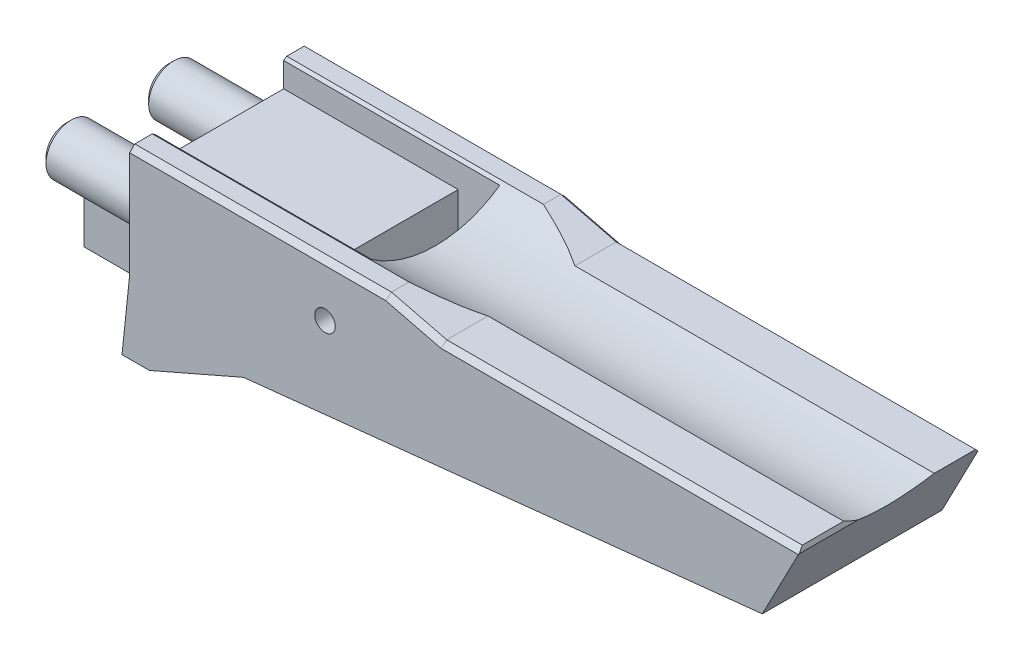
SolidWorks part; units mm, degrees
ref_plane "정면" through (0, 0, 0) normal (0, 0, 1) x (1, 0, 0)
ref_plane "윗면" through (0, 0, 0) normal (0, 1, 0) x (1, 0, 0)
ref_plane "우측면" through (0, 0, 0) normal (1, 0, 0) x (0, 0, -1)
sketch "스케치1" plane through (0, 0, 0) normal (0, 0, 1) x (1, 0, 0)
  line L0 (0, 0) -> (50, 0)
  line L1 (50, 0) -> (60.7742, -2.6631)
  line L2 (60.7742, -2.6631) -> (130.7742, -2.6631)
  line L3 (130.7742, -2.6631) -> (123.2398, -17.1695)
  line L4 (123.2398, -17.1695) -> (22.1682, -27.7991)
  line L5 (0, 0) -> (0, -21.57)
  line L6 (0, -21.57) -> (-1.496, -35.8031)
  line L7 (-1.496, -35.8031) -> (3.8284, -35.8031)
  line L8 (3.8284, -35.8031) -> (22.1682, -27.7991)
  dimension "D1" = 174
  dimension "D2" = 50
  dimension "D3" = 70
  dimension "D4" = 21.57
extrude "보스-돌출1" add sketch "스케치1" along normal mid plane 35 contours L0 L1 L2 L3 L4 L8 L7 L6 L5
sketch "스케치2" plane through (0, 0, 0) normal (0, 0, 1) x (1, 0, 0)
  line L0 (0, 0) -> (0, -5.2)
  line L1 (0, 0) -> (0, -21.57) construction
  line L2 (0, -5.2) -> (34, -5.2)
  line L3 (34, -5.2) -> (34, -18.4)
  line L4 (34, -18.4) -> (42.1, -18.4)
  line L5 (42.1, -18.4) -> (42.1, 0)
  line L6 (0, 0) -> (50, 0) construction
  line L7 (42.1, 0) -> (0, 0)
  dimension "D1" = 8.1
  dimension "D2" = 42.1
  dimension "D3" = 18.4
  dimension "D4" = 5.2
extrude "컷-돌출1" cut sketch "스케치2" against normal mid plane 25 contours L2 L3 L4 L5 L7 L0
sketch "스케치3" plane through (0, 0, 0) normal (1, 0, 0) x (0, 0, -1)
  line L0 (0, 0) -> (0, 25.9208) construction
  line L2 (13.1, 0) -> (-13.1, 0)
  line L3 (12.5, 0) -> (17.5, 0) construction
  line L4 (-17.5, 0) -> (-12.5, 0) construction
  arc A0 (-13.1, 0) -> (13.1, 0) centre (0, 17.4528) ccw
  dimension "D1" = 26.2
extrude "컷-돌출2" cut sketch "스케치3" along normal blind 135
chamfer "모따기1" distance 1 angle 45 6 edges at (95.7742, -2.6631, 17.5) (55.3871, -1.3315, 17.5) (25, 0, 17.5) (25, 0, -17.5) (55.3871, -1.3315, -17.5) (95.7742, -2.6631, -17.5)
sketch "스케치4" plane through (0, 0, 0) normal (-1, 0, 0) x (0, 0, 1)
  line L0 (0, 0) -> (0, -41.2844) construction
  line L1 (17.5, -21.57) -> (-17.5, -21.57) construction
  line L3 (-7.45, -31.37) -> (7.45, -31.37)
  line L4 (-7.45, -31.37) -> (-7.45, -21.57)
  line L5 (-7.45, -21.57) -> (7.45, -21.57)
  line L6 (7.45, -31.37) -> (7.45, -21.57)
  line L7 (-7.45, -31.37) -> (7.45, -21.57) construction
  line L8 (-7.45, -21.57) -> (7.45, -31.37) construction
  circle A0 centre (10, -13.57) radius 4.9
  circle A1 centre (-10, -13.57) radius 4.9
  point P10 (0, -26.47)
  dimension "D1" = 9.8
  dimension "D2" = 10
  dimension "D3" = 8
  dimension "D4" = 9.8
  dimension "D5" = 14.9
extrude "보스-돌출2" add sketch "스케치4" along normal blind 19.9
chamfer "모따기2" distance 1 angle 45 6 edges at (-19.9, -31.37, 0) (-19.9, -26.47, 7.45) (-19.9, -26.47, -7.45) (-19.9, -21.57, 0) (-19.9, -18.47, 10) (-19.9, -8.67, -10)
sketch "스케치8" plane through (0, 0, 17.5) normal (0, 0, 1) x (1, 0, 0)
  line L0 (34, -18.4) -> (42.1, -18.4) construction
  line L1 (34, -18.4) -> (42.1, -18.4) construction
  circle A0 centre (38.05, -10.3) radius 2
  point P2 (38.05, -18.4)
  dimension "D1" = 4
  dimension "D2" = 0
  dimension "D3" = 8.1
extrude "컷-돌출5" cut sketch "스케치8" against normal through all
